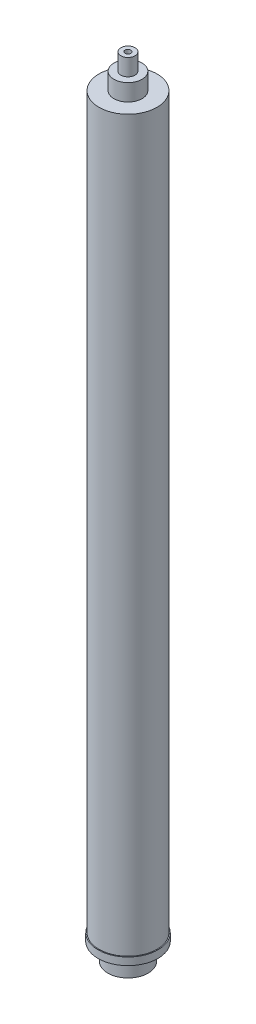
SolidWorks part; units mm, degrees
material "6061 Alloy"
ref_plane "Front Plane" through (0, 0, 0) normal (0, 0, 1) x (1, 0, 0)
ref_plane "Top Plane" through (0, 0, 0) normal (0, 1, 0) x (1, 0, 0)
ref_plane "Right Plane" through (0, 0, 0) normal (1, 0, 0) x (0, 0, -1)
sketch "Sketch1" plane through (0, 0, 0) normal (1, 0, 0) x (0, 0, -1)
  line L0 (0, 0) -> (-11.938, 0)
  line L1 (-11.938, -28.575) -> (-23.876, -28.575)
  line L2 (-23.876, -28.575) -> (-23.876, -57.15)
  line L3 (-23.876, -57.15) -> (-49.2125, -57.15)
  line L4 (-49.2125, -57.15) -> (-49.2125, -1295.654)
  line L5 (-11.938, 0) -> (-11.938, -28.575)
  line L6 (0, 0) -> (0, -1338.199) construction
  line L7 (-49.2125, -1295.654) -> (-50.8, -1295.654)
  line L8 (-50.8, -1295.654) -> (-50.8, -1308.354)
  line L9 (-50.8, -1308.354) -> (-34.29, -1308.354)
  line L10 (-34.29, -1308.354) -> (-34.29, -1338.199)
  line L11 (-34.29, -1338.199) -> (0, -1338.199)
  line L12 (0, 0) -> (0, -1338.199)
  point P9 (-11.938, -14.2875)
  point P10 (-49.2125, -676.402)
  dimension "D1" = 47.752
  dimension "D2" = 23.876
  dimension "D3" = 98.425
  dimension "D4" = 101.6
  dimension "D5" = 68.58
  dimension "D6" = 29.845
  dimension "D7" = 12.7
  dimension "D8" = 1238.504
  dimension "D9" = 57.15
revolve "Revolve1" add sketch "Sketch1" angle 360 about L6
sketch "Sketch2" plane through (0, 0, 0) normal (0, 1, 0) x (1, 0, 0)
  circle A0 centre (0, 0) radius 4.95
  dimension "D1" = 9.9
extrude "Cut-Extrude1" cut sketch "Sketch2" against normal blind 25.4
cosmetic thread "Cosmetic Thread1" parameters "D2"=12.7
sketch "Sketch3" [suppressed] plane through (0, 0, 0) normal (1, 0, 0) x (0, 0, -1)
  line L0 (-50.8, -1298.194) -> (-50.8, -1303.274)
  line L1 (-50.8, -1303.274) -> (-37.719, -1342.644)
  line L2 (-37.719, -1342.644) -> (0, -1342.644)
  line L3 (0, -1342.644) -> (0, -1298.194) construction
  line L4 (-34.29, -1298.194) -> (34.29, -1298.194) construction
  line L5 (0, -1298.194) -> (-50.8, -1298.194)
  line L6 (0, -1342.644) -> (0, -1298.194)
  dimension "D1" = 5.08
  dimension "D2" = 75.438
  dimension "D3" = 44.45
revolve "Revolve2" [suppressed] add sketch "Sketch3" angle 360 about L3
sketch "Sketch4" [suppressed] plane through (0, -1342.644, 0) normal (0, -1, 0) x (1, 0, 0)
  circle A0 centre (0, 0) radius 34.719
  circle A1 centre (0, 0) radius 37.719 construction
  dimension "D1" = 3
extrude "Cut-Extrude2" [suppressed] cut sketch "Sketch4" against normal blind 50
sketch "Sketch5" plane through (0, -1338.199, 0) normal (0, -1, 0) x (1, 0, 0)
  circle A0 centre (0, 0) radius 27.5
  dimension "D1" = 55
extrude "Cut-Extrude3" cut sketch "Sketch5" against normal blind 1000
equation "\"D2@Sketch1\"=\"D1@Sketch1\"/2"
